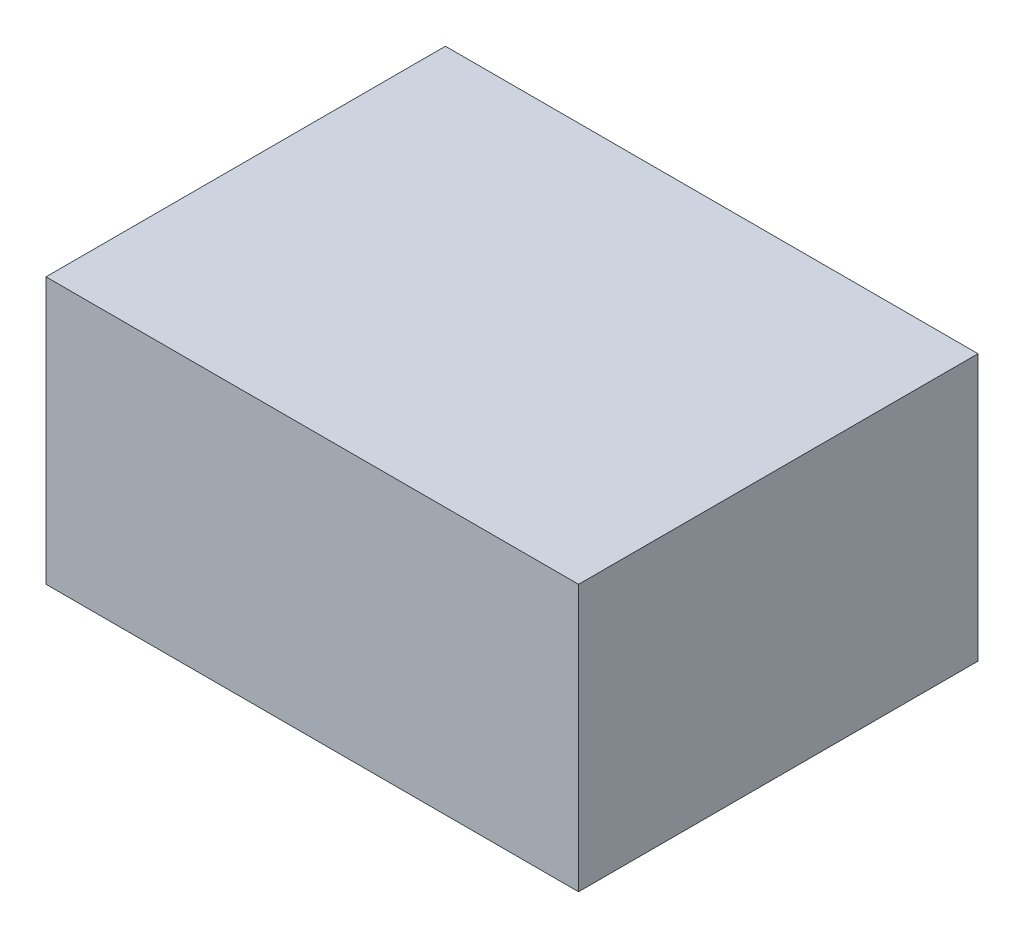
SolidWorks part; units mm, degrees
ref_plane "Front Plane" through (0, 0, 0) normal (0, 0, 1) x (1, 0, 0)
ref_plane "Top Plane" through (0, 0, 0) normal (0, 1, 0) x (1, 0, 0)
ref_plane "Right Plane" through (0, 0, 0) normal (1, 0, 0) x (0, 0, -1)
sketch "Sketch1" plane through (0, 0, 0) normal (0, 1, 0) x (1, 0, 0)
  line L1 (-60, 45) -> (0, 45)
  line L2 (-60, 45) -> (-60, 0)
  line L3 (-60, 0) -> (0, 0)
  line L4 (0, 45) -> (0, 0)
  dimension "D1" = 60
  dimension "D2" = 45
extrude "Boss-Extrude1" add sketch "Sketch1" along normal blind 30
sketch "Sketch2" plane through (0, 0, 0) normal (0, -1, 0) x (-1, 0, 0)
  line L0 (60, 45) -> (60, 0) construction
  line L1 (51, 13) -> (44.5, 13)
  line L2 (51, 13) -> (51, 29)
  line L3 (51, 29) -> (44.5, 29)
  line L4 (44.5, 13) -> (44.5, 29)
  line L5 (16, 13) -> (9.5, 13)
  line L6 (16, 13) -> (16, 29)
  line L7 (16, 29) -> (9.5, 29)
  line L8 (9.5, 13) -> (9.5, 29)
  line L10 (0, 0) -> (0, 45) construction
  line L12 (0, 45) -> (60, 45) construction
  dimension "D1" = 16
  dimension "D2" = 6.5
  dimension "D3" = 9
  dimension "D4" = 6.5
  dimension "D5" = 16
  dimension "D6" = 9.5
  dimension "D7" = 16
extrude "Cut-Extrude1" cut sketch "Sketch2" against normal blind 20
chamfer "Chamfer1" distance 5 angle 5 4 edges at (-16, 20, -21) (-9.5, 20, -21) (-51, 20, -21) (-44.5, 20, -21)
chamfer "Chamfer2" distance 5 angle 50 4 edges at (-47.75, 20, -29) (-12.75, 20, -29) (-12.75, 20, -13) (-47.75, 20, -13)
sketch "Sketch4" plane through (0, 0, -45) normal (0, 0, -1) x (-1, 0, 0)
  line L0 (12.7, 0) -> (29.5, 0)
  line L1 (0, 0) -> (60, 0) construction
  arc A0 (29.5, 0) -> (43.8119, 6.1301) centre (39.3836, -3.3031) cw
  arc A1 (43.8119, 6.1301) -> (47.4306, 12.0745) centre (45.2992, 9.2984) ccw
  arc A2 (47.4306, 12.0745) -> (12.7, 0) centre (34.0331, -5.3756) ccw
  dimension "D3" = 3.5
  dimension "D4" = 10.4209
  dimension "D7" = 22
  dimension "D1" = 16.8
  dimension "D2" = 15
  dimension "D5" = 3.3031
  dimension "D6" = 9.2984
extrude "Cut-Extrude2" cut sketch "Sketch4" against normal blind 10
chamfer "Chamfer3" distance 3 distance2 2 8 edges at (-12.75, 0, -13) (-9.5, 0, -21) (-12.75, 0, -29) (-16, 0, -21) (-47.75, 0, -29) (-44.5, 0, -21) (-47.75, 0, -13) (-51, 0, -21)
